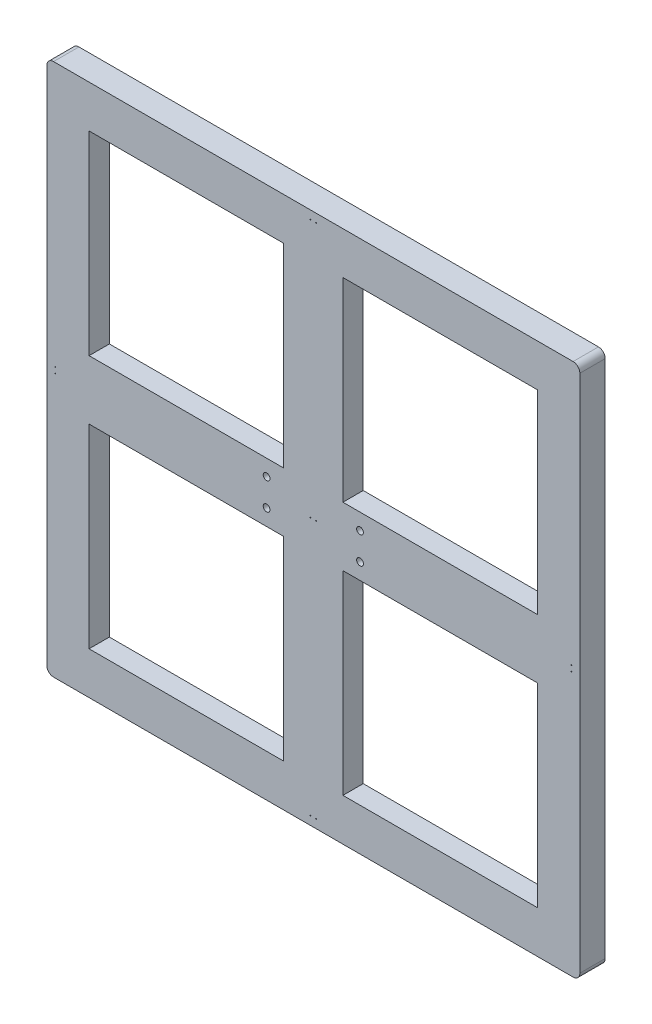
SolidWorks part; units mm, degrees
material "Cedar"
ref_plane "Plan de face" through (0, 0, 0) normal (0, 0, 1) x (1, 0, 0)
ref_plane "Plan de dessus" through (0, 0, 0) normal (0, 1, 0) x (1, 0, 0)
ref_plane "Plan de droite" through (0, 0, 0) normal (1, 0, 0) x (0, 0, -1)
sketch "Sketch1" plane through (0, 0, 0) normal (0, 0, 1) x (1, 0, 0)
  line L5 (-157.5, 157.5) -> (157.5, 157.5)
  line L6 (-147.5, 147.5) -> (-2.5, 147.5)
  line L11 (-147.5, 147.5) -> (-147.5, 2.5)
  line L12 (-147.5, -147.5) -> (-2.5, -147.5)
  line L17 (147.5, 147.5) -> (147.5, 2.5)
  line L18 (-147.5, 147.5) -> (-2.5, 2.5) construction
  line L27 (-147.5, -147.5) -> (-2.5, -2.5) construction
  line L28 (157.5, 157.5) -> (157.5, -157.5)
  line L29 (-157.5, -157.5) -> (157.5, -157.5)
  line L30 (-157.5, 157.5) -> (-157.5, 2.5)
  line L31 (2.5, 147.5) -> (147.5, 147.5)
  line L37 (-147.5, 147.5) -> (147.5, 147.5) construction
  line L42 (-157.5, 2.5) -> (-157.5, -2.5)
  line L43 (147.5, -2.5) -> (147.5, -147.5)
  line L45 (-147.5, 2.5) -> (-2.5, 2.5)
  line L48 (-147.5, -2.5) -> (-2.5, -2.5)
  line L49 (-147.5, -2.5) -> (-147.5, -147.5)
  line L50 (-147.5, 147.5) -> (-147.5, -147.5) construction
  line L51 (-157.5, -2.5) -> (-157.5, -157.5)
  line L52 (-157.5, 157.5) -> (-157.5, -157.5) construction
  line L53 (147.5, 147.5) -> (147.5, -147.5) construction
  line L54 (2.5, -147.5) -> (147.5, -147.5)
  line L55 (-147.5, -147.5) -> (147.5, -147.5) construction
  line L57 (-2.5, -147.5) -> (-2.5, -2.5)
  line L59 (2.5, -147.5) -> (2.5, -2.5)
  line L60 (2.5, -2.5) -> (147.5, -147.5) construction
  line L61 (-2.5, 2.5) -> (-2.5, 147.5)
  line L63 (2.5, 2.5) -> (147.5, 147.5) construction
  line L65 (2.5, -2.5) -> (147.5, -2.5)
  line L67 (2.5, 2.5) -> (2.5, 147.5)
  line L68 (2.5, 2.5) -> (147.5, 2.5)
  point P0 (0, 0)
  point P9 (0, 0)
  point P14 (0, 0)
  dimension "D1" = 295
  dimension "D2" = 10
extrude "Boss-Extrude2" add sketch "Sketch1" along normal mid plane 15
sketch "Sketch3" plane through (0, 0, 7.5) normal (0, 0, 1) x (1, 0, 0)
  line L0 (-147.5, -147.5) -> (-2.5, -147.5) construction
  line L1 (-147.5, -2.5) -> (-147.5, -147.5) construction
  line L2 (-2.5, -2.5) -> (-147.5, -2.5) construction
  line L3 (-2.5, -147.5) -> (-2.5, -2.5) construction
  line L4 (2.5, -2.5) -> (2.5, -147.5) construction
  line L5 (2.5, -147.5) -> (147.5, -147.5) construction
  line L6 (147.5, -147.5) -> (147.5, -2.5) construction
  line L7 (147.5, -2.5) -> (2.5, -2.5) construction
  line L8 (2.5, 2.5) -> (147.5, 2.5) construction
  line L9 (147.5, 2.5) -> (147.5, 147.5) construction
  line L10 (147.5, 147.5) -> (2.5, 147.5) construction
  line L11 (2.5, 147.5) -> (2.5, 2.5) construction
  line L12 (-147.5, 147.5) -> (-147.5, 2.5) construction
  line L13 (-147.5, 2.5) -> (-2.5, 2.5) construction
  line L14 (-2.5, 2.5) -> (-2.5, 147.5) construction
  line L15 (-2.5, 147.5) -> (-147.5, 147.5) construction
  line L16 (-147.5, -147.5) -> (-2.5, -147.5)
  line L17 (-147.5, -2.5) -> (-147.5, -147.5)
  line L18 (-2.5, -2.5) -> (-147.5, -2.5)
  line L19 (-2.5, -147.5) -> (-2.5, -2.5)
  line L20 (2.5, -2.5) -> (2.5, -147.5)
  line L21 (2.5, -147.5) -> (147.5, -147.5)
  line L22 (147.5, -147.5) -> (147.5, -2.5)
  line L23 (147.5, -2.5) -> (2.5, -2.5)
  line L24 (2.5, 2.5) -> (147.5, 2.5)
  line L25 (147.5, 2.5) -> (147.5, 147.5)
  line L26 (147.5, 147.5) -> (2.5, 147.5)
  line L27 (2.5, 147.5) -> (2.5, 2.5)
  line L28 (-147.5, 147.5) -> (-147.5, 2.5)
  line L29 (-147.5, 2.5) -> (-2.5, 2.5)
  line L30 (-2.5, 2.5) -> (-2.5, 147.5)
  line L31 (-2.5, 147.5) -> (-147.5, 147.5)
  line L32 (-17.5, 132.5) -> (-132.5, 132.5)
  line L33 (-132.5, 132.5) -> (-132.5, 17.5)
  line L34 (-132.5, 17.5) -> (-17.5, 17.5)
  line L35 (-17.5, 17.5) -> (-17.5, 132.5)
  line L36 (132.5, 132.5) -> (17.5, 132.5)
  line L37 (17.5, 132.5) -> (17.5, 17.5)
  line L38 (17.5, 17.5) -> (132.5, 17.5)
  line L39 (132.5, 17.5) -> (132.5, 132.5)
  line L40 (132.5, -17.5) -> (17.5, -17.5)
  line L41 (17.5, -17.5) -> (17.5, -132.5)
  line L42 (17.5, -132.5) -> (132.5, -132.5)
  line L43 (132.5, -132.5) -> (132.5, -17.5)
  line L44 (-17.5, -132.5) -> (-17.5, -17.5)
  line L45 (-17.5, -17.5) -> (-132.5, -17.5)
  line L46 (-132.5, -17.5) -> (-132.5, -132.5)
  line L47 (-132.5, -132.5) -> (-17.5, -132.5)
  dimension "D1" = 15
extrude "Boss-Extrude4" add sketch "Sketch3" against normal blind 12
sketch "Sketch4" plane through (0, 0, -7.5) normal (0, 0, -1) x (-1, 0, 0)
  line L0 (0, 0) -> (0, 152.5) construction
  line L2 (-157.5, 157.5) -> (157.5, 157.5) construction
  line L3 (-1.7, 152.5) -> (1.7, 152.5) construction
  line L4 (-1.7, 0) -> (1.7, 0) construction
  line L5 (-171.8084, 0) -> (239.6486, 0) construction
  line L6 (-152.5, 1.7) -> (-152.5, -1.7) construction
  line L7 (-157.5, -157.5) -> (-157.5, 157.5) construction
  line L8 (-1.7, -152.5) -> (1.7, -152.5) construction
  line L9 (152.5, 1.7) -> (152.5, -1.7) construction
  circle A0 centre (-1.7, 152.5) radius 0.275
  circle A1 centre (1.7, 152.5) radius 0.275
  circle A2 centre (-1.7, 0) radius 0.275
  circle A3 centre (1.7, 0) radius 0.275
  circle A4 centre (-152.5, 1.7) radius 0.275
  circle A5 centre (-152.5, -1.7) radius 0.275
  circle A6 centre (1.7, -152.5) radius 0.275
  circle A7 centre (-1.7, -152.5) radius 0.275
  circle A8 centre (152.5, -1.7) radius 0.275
  circle A9 centre (152.5, 1.7) radius 0.275
  point P8 (0, 152.5)
  point P12 (0, 0)
  point P21 (-152.5, 0)
  dimension "D3" = 0.55
  dimension "D5" = 0.55
  dimension "D8" = 0.55
  dimension "D9" = 0.55
  dimension "D1" = 5
  dimension "D2" = 3.4
  dimension "D4" = 3.4
  dimension "D6" = 5
  dimension "D7" = 3.4
extrude "Cut-Extrude1" cut sketch "Sketch4" against normal through all
sketch "Sketch5" plane through (0, 0, 7.5) normal (0, 0, 1) x (1, 0, 0)
  line L0 (0, 0) -> (-27.6, 0) construction
  line L1 (-27.6, 8) -> (-27.6, -8) construction
  line L2 (0, 0) -> (0, 27.2907) construction
  line L3 (27.6, 8) -> (27.6, -8) construction
  circle A0 centre (-27.6, -8) radius 2
  circle A1 centre (-27.6, 8) radius 2
  circle A2 centre (27.6, 8) radius 2
  circle A3 centre (27.6, -8) radius 2
  dimension "D1" = 4
  dimension "D2" = 8
  dimension "D3" = 27.6
extrude "Cut-Extrude2" cut sketch "Sketch5" against normal through all
fillet "Fillet1" radius 4 4 edges at (-157.5, -157.5, 0) (157.5, -157.5, 0) (157.5, 157.5, 0) (-157.5, 157.5, 0)
